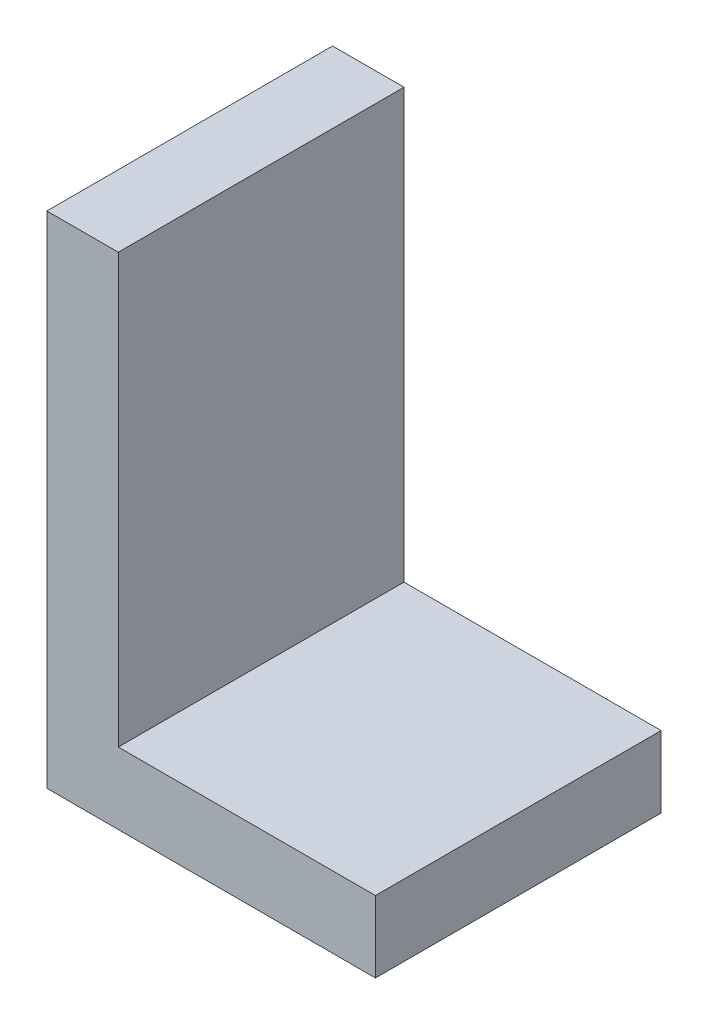
SolidWorks part; units mm, degrees
ref_plane "Plano frontal" through (0, 0, 0) normal (0, 0, 1) x (1, 0, 0)
ref_plane "Plano superior" through (0, 0, 0) normal (0, 1, 0) x (1, 0, 0)
ref_plane "Plano direito" through (0, 0, 0) normal (1, 0, 0) x (0, 0, -1)
sketch "Esboço1" plane through (0, 0, 0) normal (0, 0, 1) x (1, 0, 0)
  line L0 (0, 0) -> (0, 700)
  line L1 (0, 700) -> (100, 700)
  line L2 (100, 700) -> (100, 100)
  line L3 (100, 100) -> (460, 100)
  line L4 (460, 100) -> (460, 0)
  line L5 (460, 0) -> (0, 0)
  dimension "D1" = 100
  dimension "D2" = 100
  dimension "D3" = 600
  dimension "D4" = 460
extrude "Ressalto-extrusão1" add sketch "Esboço1" along normal blind 400
